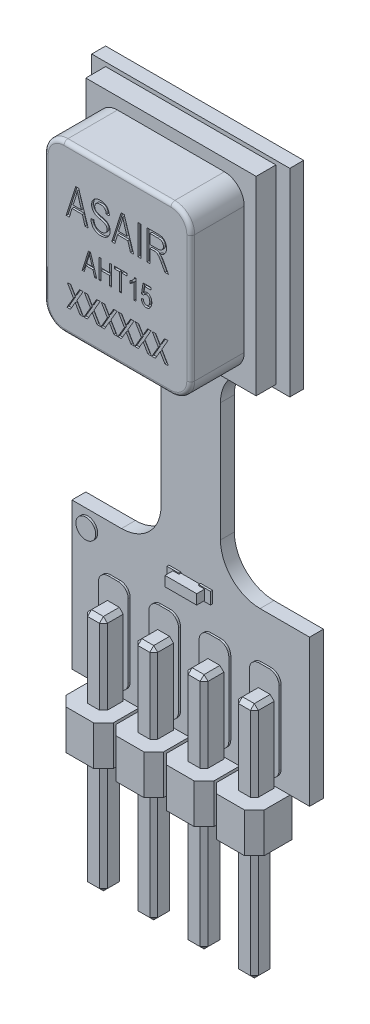
SolidWorks part; units mm, degrees
ref_plane "Alzado" through (0, 0, 0) normal (0, 0, 1) x (1, 0, 0)
ref_plane "Planta" through (0, 0, 0) normal (0, 1, 0) x (1, 0, 0)
ref_plane "Vista lateral" through (0, 0, 0) normal (1, 0, 0) x (0, 0, -1)
sketch "Sketch1" plane through (0, 0, 0) normal (0, 0, 1) x (1, 0, 0)
  line L0 (-7.0612, 0.7821) -> (18.5993, 0.7821) construction
  line L1 (-0.75, -2.5) -> (-0.75, -7.5)
  line L2 (-2.5, 2.5) -> (2.5, 2.5)
  line L3 (-2.5, 2.5) -> (-2.5, -2.5)
  line L4 (-2.5, -2.5) -> (2.5, -2.5)
  line L5 (2.5, 2.5) -> (2.5, -2.5)
  line L6 (0, -2.5) -> (0, 2.5) construction
  line L7 (-2.5, 0) -> (2.5, 0) construction
  line L8 (-0.75, -7.5) -> (-3, -7.5)
  line L9 (-3, -7.5) -> (-3, -11.2)
  line L10 (-3, -11.2) -> (3, -11.2)
  line L11 (3, -11.2) -> (3, -7.5)
  line L12 (3, -7.5) -> (0.75, -7.5)
  line L13 (0.75, -7.5) -> (0.75, -2.5)
  line L14 (-0.75, -7.5) -> (0.75, -7.5) construction
  point P2 (0, 0)
  point P13 (0, -7.5)
  dimension "D1" = 5
  dimension "D2" = 5
  dimension "D3" = 1.5
  dimension "D4" = 6
  dimension "D5" = 3.7
  dimension "D6" = 5
extrude "Boss-Extrude1" add sketch "Sketch1" against normal blind 0.35 contours L5 L2 L3 L4 | L12 L13 L4 L1 L8 L9 L10 L11
fillet "Fillet1" radius 1 4 edges at (0.75, -2.5, -0.175) (-0.75, -2.5, -0.175) (-0.75, -7.5, -0.175) (0.75, -7.5, -0.175)
sketch "Sketch2" plane through (0, 0, 0) normal (1, 0, 0) x (0, 0, -1)
  line L0 (-4.4118, -17.9701) -> (-4.4118, 13.5701) construction
sketch "Sketch6" plane through (0, 0, 0) normal (0, 0, 1) x (1, 0, 0)
  line L1 (-1.85, 2.1) -> (1.85, 2.1)
  line L2 (-1.85, 2.1) -> (-1.85, -2.1)
  line L3 (-1.85, -2.1) -> (1.85, -2.1)
  line L4 (1.85, 2.1) -> (1.85, -2.1)
  line L5 (0, -2.1) -> (0, 2.1) construction
  line L6 (-1.85, 0) -> (1.85, 0) construction
  point P0 (0, 0)
  dimension "D1" = 4.2
  dimension "D2" = 3.7
extrude "Boss-Extrude3" add sketch "Sketch6" along normal blind 2.2 from surface at -0.35 starting at face at (0, -4.8375, -0.35)
sketch "Sketch3" plane through (0, 0, 0) normal (0, 0, 1) x (1, 0, 0)
  line L1 (-2.15, 2.4) -> (2.15, 2.4)
  line L2 (-2.15, 2.4) -> (-2.15, -2.4)
  line L3 (-2.15, -2.4) -> (2.15, -2.4)
  line L4 (2.15, 2.4) -> (2.15, -2.4)
  line L5 (0, -2.4) -> (0, 2.4) construction
  line L6 (-2.15, 0) -> (2.15, 0) construction
  point P0 (0, 0)
  dimension "D1" = 4.8
  dimension "D2" = 4.3
extrude "Boss-Extrude2" add sketch "Sketch3" along normal blind 0.5
fillet "Fillet2" radius 0.5 4 edges at (1.85, 2.1, 1.175) (-1.85, 2.1, 1.175) (-1.85, -2.1, 1.175) (1.85, -2.1, 1.175)
fillet "Fillet3" radius 0.1 8 edges at (-1.7036, 1.9536, 1.85) (0, 2.1, 1.85) (1.7036, 1.9536, 1.85) (1.85, 0, 1.85) (1.7036, -1.9536, 1.85) (0, -2.1, 1.85) (-1.7036, -1.9536, 1.85) (-1.85, 0, 1.85)
sketch "Sketch7" plane through (0, 0, 0) normal (0, 0, 1) x (1, 0, 0)
  line L0 (-1.01, -9.825) -> (-1.53, -9.825) construction
  line L1 (-2.28, -8.65) -> (-1.53, -8.65)
  line L2 (-2.28, -8.65) -> (-2.28, -11)
  line L3 (-2.28, -11) -> (-1.53, -11)
  line L4 (-1.53, -8.65) -> (-1.53, -11)
  line L5 (-1.01, -8.65) -> (-0.26, -8.65)
  line L6 (-1.01, -8.65) -> (-1.01, -11)
  line L7 (-1.01, -11) -> (-0.26, -11)
  line L8 (-0.26, -8.65) -> (-0.26, -11)
  line L9 (0.26, -8.65) -> (1.01, -8.65)
  line L10 (0.26, -8.65) -> (0.26, -11)
  line L11 (0.26, -11) -> (1.01, -11)
  line L12 (1.01, -8.65) -> (1.01, -11)
  line L13 (1.53, -8.65) -> (2.28, -8.65)
  line L14 (1.53, -8.65) -> (1.53, -11)
  line L15 (1.53, -11) -> (2.28, -11)
  line L16 (2.28, -8.65) -> (2.28, -11)
  line L17 (-0.26, -9.825) -> (0.26, -9.825) construction
  line L18 (1.01, -9.825) -> (1.53, -9.825) construction
  line L19 (-3, -11.2) -> (3, -11.2) construction
  line L20 (-0.75, -7.5) -> (-3, -7.5) construction
  line L21 (-3, -7.5) -> (-3, -11.2) construction
  line L22 (-0.25, -7.85) -> (0.25, -7.85) construction
  line L23 (-0.55, -7.7) -> (-0.25, -7.7)
  line L24 (-0.55, -7.7) -> (-0.55, -8)
  line L25 (-0.55, -8) -> (-0.25, -8)
  line L26 (-0.25, -7.7) -> (-0.25, -8)
  line L27 (0.25, -7.7) -> (0.55, -7.7)
  line L28 (0.25, -7.7) -> (0.25, -8)
  line L29 (0.25, -8) -> (0.55, -8)
  line L30 (0.55, -7.7) -> (0.55, -8)
  line L31 (3, -7.5) -> (0.75, -7.5) construction
  circle A0 centre (-2.6, -7.9) radius 0.25
  point P22 (0, -9.825)
  point P42 (0, -7.85)
  dimension "D5" = 0.5
  dimension "D6" = 0.4
  dimension "D1" = 2.35
  dimension "D2" = 0.75
  dimension "D3" = 1.27
  dimension "D4" = 0.2
  dimension "D7" = 0.4
  dimension "D8" = 0.3
  dimension "D9" = 0.5
  dimension "D10" = 0.35
extrude "Boss-Extrude4" add sketch "Sketch7" along normal blind 0.05
fillet "Fillet4" radius 0.25 16 edges at (-1.53, -11, 0.025) (-2.28, -11, 0.025) (-2.28, -8.65, 0.025) (-1.53, -8.65, 0.025) (-0.26, -8.65, 0.025) (-1.01, -8.65, 0.025) (-1.01, -11, 0.025) (-0.26, -11, 0.025) (0.26, -11, 0.025) (0.26, -8.65, 0.025) (1.01, -8.65, 0.025) (1.01, -11, 0.025) (1.53, -11, 0.025) (2.28, -11, 0.025) (1.53, -8.65, 0.025) (2.28, -8.65, 0.025)
sketch "Sketch8" plane through (0, 0, 0) normal (0, 0, 1) x (1, 0, 0)
  line L1 (-0.4, -7.725) -> (0.4, -7.725)
  line L2 (-0.4, -7.725) -> (-0.4, -7.975)
  line L3 (-0.4, -7.975) -> (0.4, -7.975)
  line L4 (0.4, -7.725) -> (0.4, -7.975)
  line L6 (-0.25, -7.7) -> (-0.55, -7.7) construction
  line L7 (0.55, -7.7) -> (0.25, -7.7) construction
  line L8 (-0.55, -7.7) -> (-0.55, -8) construction
  point P9 (-0.4, -7.7)
  point P13 (0.4, -7.7)
  point P16 (-0.55, -7.85)
  point P17 (-0.4, -7.85)
  dimension "D1" = 0.25
extrude "Boss-Extrude5" add sketch "Sketch8" along normal blind 0.25
sketch "Sketch9" plane through (0, -11.2, 0) normal (0, -1, 0) x (1, 0, 0)
  line L1 (-2.505, 0.9) -> (-1.305, 0.9)
  line L2 (-2.505, 0.9) -> (-2.505, -0.3)
  line L3 (-2.505, -0.3) -> (-1.305, -0.3)
  line L4 (-1.305, 0.9) -> (-1.305, -0.3)
  line L5 (-1.905, -0.3) -> (-1.905, 0.9) construction
  line L6 (-2.505, 0.3) -> (-1.305, 0.3) construction
  line L7 (-2.03, 0.05) -> (-1.78, 0.05) construction
  line L8 (-3, 0) -> (3, 0) construction
  point P0 (-1.905, 0.3)
  point P11 (-1.905, 0.05)
  dimension "D1" = 1.2
  dimension "D2" = 0.3
extrude "Boss-Extrude6" add sketch "Sketch9" along normal blind 1
chamfer "Chamfer1" distance 0.25 angle 45 4 edges at (-1.305, -11.7, -0.3) (-2.505, -11.7, -0.3) (-1.305, -11.7, 0.9) (-2.505, -11.7, 0.9)
sketch "Sketch10" plane through (0, -12.2, 0) normal (0, -1, 0) x (1, 0, 0)
  line L0 (-1.305, -0.05) -> (-1.305, 0.65) construction
  line L1 (-2.155, 0.55) -> (-1.655, 0.55)
  line L2 (-2.155, 0.55) -> (-2.155, 0.05)
  line L3 (-2.155, 0.05) -> (-1.655, 0.05)
  line L4 (-1.655, 0.55) -> (-1.655, 0.05)
  line L5 (-1.905, 0.05) -> (-1.905, 0.55) construction
  line L6 (-2.155, 0.3) -> (-1.655, 0.3) construction
  line L7 (-1.555, 0.9) -> (-2.255, 0.9) construction
  point P0 (-1.905, 0.3)
  point P7 (-1.305, 0.3)
  point P13 (-1.905, 0.9)
  dimension "D1" = 0.5
extrude "Boss-Extrude7" add sketch "Sketch10" along normal blind 3 and the other way blind 3
chamfer "Chamfer2" distance 0.1 angle 45 13 edges at (-2.155, -9.2, 0.3) (-1.655, -9.2, 0.3) (-2.155, -10.2, 0.55) (-1.905, -9.2, 0.55) (-1.655, -10.2, 0.55) (-1.905, -15.2, 0.05) (-2.155, -13.7, 0.05) (-2.155, -15.2, 0.3) (-2.155, -13.7, 0.55) (-1.905, -15.2, 0.55) (-1.655, -13.7, 0.05) (-1.655, -15.2, 0.3) (-1.655, -13.7, 0.55)
pattern_linear "LPattern1" count 4 spacing 1.27 along (1, 0, 0) of "Boss-Extrude6", "Chamfer1", "Boss-Extrude7", "Chamfer2"
sketch "Sketch11" plane through (0, 0, 1.85) normal (0, 0, 1) x (1, 0, 0)
  line L0 (-1.5, 0.5) -> (1.5, 0.5) construction
  line L1 (-1.5, -0.5) -> (1.5, -0.5) construction
  line L2 (-1.5, -1.5) -> (1.5, -1.5) construction
  text T0 "ASAIR" font "Arial Narrow" height 0.75
  text T1 "AHT15" font "Arial Narrow" height 0.5
  text T2 "xxxxxx" font "Arial Narrow" height 0.75
  point P3 (0, -0.5)
  point P4 (0, 0.5)
  point P8 (0, -1.5)
  dimension "D1" = 0.5
  dimension "D2" = 3
  dimension "D3" = 1
  dimension "D4" = 1
extrude "Cut-Extrude1" cut sketch "Sketch11" against normal blind 0.05
